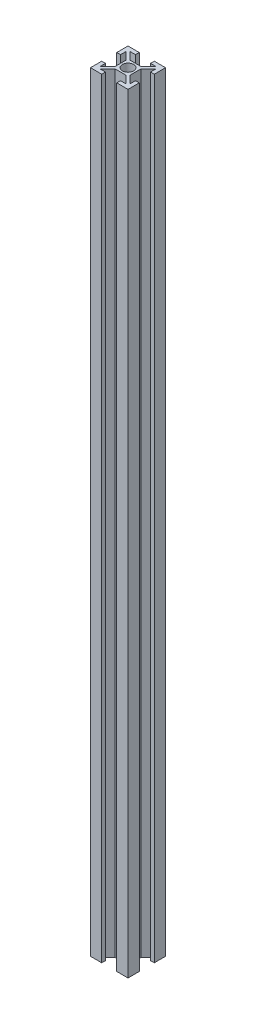
SolidWorks part; units mm, degrees
material "1060 Alloy"
ref_plane "Front Plane" through (0, 0, 0) normal (0, 0, 1) x (1, 0, 0)
ref_plane "Top Plane" through (0, 0, 0) normal (0, 1, 0) x (1, 0, 0)
ref_plane "Right Plane" through (0, 0, 0) normal (1, 0, 0) x (0, 0, -1)
sketch "Sketch1" plane through (0, 0, 0) normal (0, 0, 1) x (1, 0, 0)
  line L0 (18.2498, -12.1687) -> (243.1097, 212.6913) construction
  line L1 (243.1097, 212.6913) -> (18.2498, 437.5512) construction
  dimension "D1" = 318
  dimension "D2" = 318
  dimension "D3" = 90
sketch "2020 sketch" plane through (0, 0, 0) normal (0, 1, 0) x (1, 0, 0)
  line L0 (-4, 10) -> (-4, 8)
  line L1 (-10, 10) -> (-4, 10)
  line L2 (-10, 10) -> (-10, 4)
  line L3 (-10, -10) -> (-4, -10)
  line L4 (10, 10) -> (10, 4)
  line L5 (-10, 10) -> (10, -10) construction
  line L6 (-10, -10) -> (10, 10) construction
  line L7 (-4, 8) -> (-7, 8)
  line L8 (-7, 8) -> (-3, 4)
  line L9 (-3, 4) -> (3, 4)
  line L10 (3, 4) -> (7, 8)
  line L11 (7, 8) -> (4, 8)
  line L12 (4, 8) -> (4, 10)
  line L13 (4, 3) -> (4, -3)
  line L14 (8, 7) -> (4, 3)
  line L15 (8, 4) -> (8, 7)
  line L16 (10, 4) -> (8, 4)
  line L17 (8, -4) -> (10, -4)
  line L18 (8, -7) -> (8, -4)
  line L19 (4, -3) -> (8, -7)
  line L20 (3, -4) -> (-3, -4)
  line L21 (7, -8) -> (3, -4)
  line L22 (4, -8) -> (7, -8)
  line L23 (4, -10) -> (4, -8)
  line L24 (-4, -8) -> (-4, -10)
  line L25 (-7, -8) -> (-4, -8)
  line L26 (-3, -4) -> (-7, -8)
  line L27 (-4, -3) -> (-4, 3)
  line L28 (-8, -7) -> (-4, -3)
  line L29 (-8, -4) -> (-8, -7)
  line L30 (-10, -4) -> (-8, -4)
  line L31 (-8, 4) -> (-10, 4)
  line L32 (-8, 7) -> (-8, 4)
  line L33 (-4, 3) -> (-8, 7)
  line L34 (-10, -4) -> (-10, -10)
  line L35 (10, -4) -> (10, -10)
  line L36 (4, 10) -> (10, 10)
  line L37 (4, -10) -> (10, -10)
  circle A0 centre (0, 0) radius 3
  point P0 (0, 0)
  point P14 (4, 9)
  point P42 (0, 0)
  dimension "D9" = 6
  dimension "D1" = 20
  dimension "D2" = 20
  dimension "D3" = 8
  dimension "D4" = 6
  dimension "D5" = 6
  dimension "D6" = 2
  dimension "D7" = 4
  dimension "D8" = 4
extrude "Boss-Extrude1" add sketch "2020 sketch" along normal blind 410 from vertex at -12.1687 contours A0 | L28 L27 L33 L32 L31 L2 L1 L0 L7 L8 L9 L10 L11 L12 L36 L4 L16 L15 L14 L13 L19 L18 L17 L35 L37 L23 L22 L21 L20 L26 L25 L24 L3 L34 L30 L29
